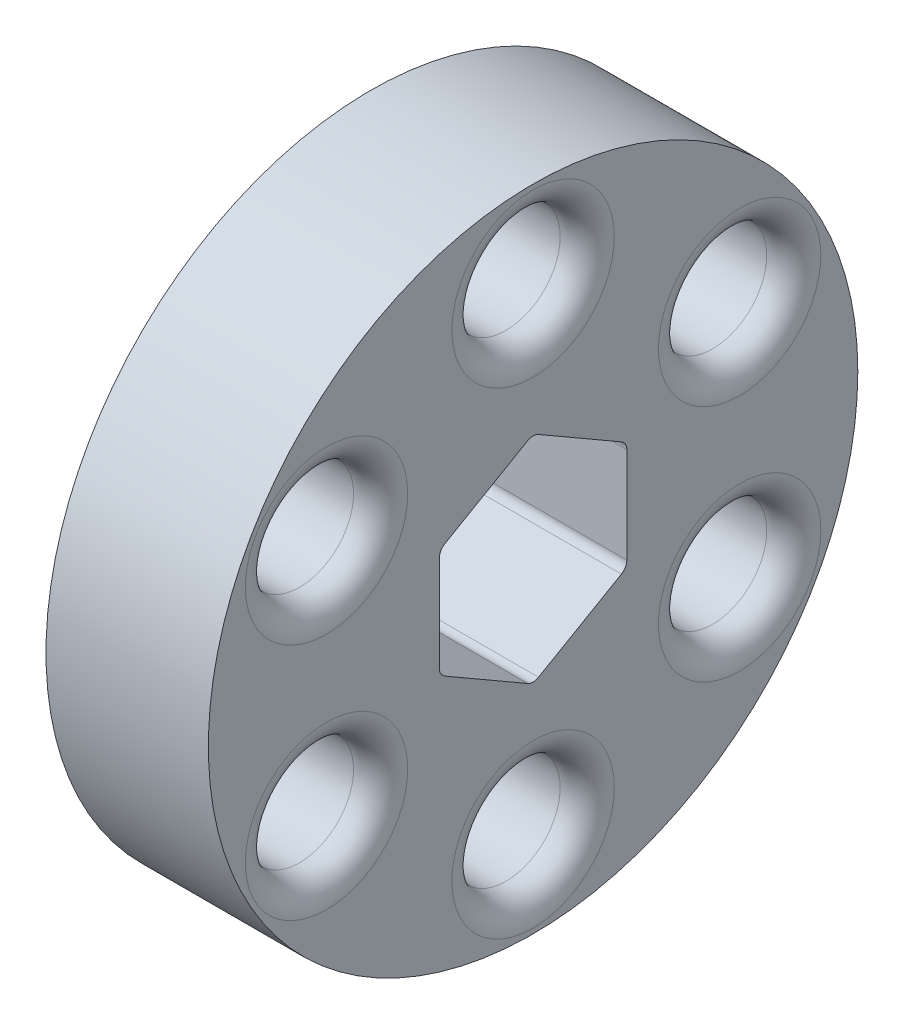
SolidWorks part; units mm, degrees
material "Náilon 6/10"
ref_plane "Plano frontal" through (0, 0, 0) normal (0, 0, 1) x (1, 0, 0)
ref_plane "Plano superior" through (0, 0, 0) normal (0, 1, 0) x (1, 0, 0)
ref_plane "Plano direito" through (0, 0, 0) normal (1, 0, 0) x (0, 0, -1)
sketch "Esboço1" plane through (0, 0, 0) normal (1, 0, 0) x (0, 0, -1)
  circle A0 centre (0, 0) radius 30
extrude "Ressalto-extrusão1" add sketch "Esboço1" along normal blind 15
sketch "Esboço2" plane through (15, 0, 0) normal (1, 0, 0) x (0, 0, -1)
  line L1 (0, 10) -> (-8.6603, 5)
  line L2 (-8.6603, 5) -> (-8.6603, -5)
  line L3 (-8.6603, -5) -> (0, -10)
  line L4 (0, -10) -> (8.6603, -5)
  line L5 (8.6603, -5) -> (8.6603, 5)
  line L6 (8.6603, 5) -> (0, 10)
  circle A0 centre (0, 0) radius 8.6603 construction
  circle A1 centre (0, 22.0357) radius 5
  circle A2 centre (19.0835, 11.0178) radius 5
  circle A3 centre (19.0835, -11.0178) radius 5
  circle A4 centre (0, -22.0357) radius 5
  circle A5 centre (-19.0835, -11.0178) radius 5
  circle A6 centre (-19.0835, 11.0178) radius 5
  point P24 (0, 0)
  dimension "D2" = 6
  dimension "D1" = 10
extrude "Corte-extrusão3" cut sketch "Esboço2" against normal through all
fillet "Filete1" radius 2.5 12 edges at (15, 11.0178, 14.0835) (0, 11.0178, 14.0835) (15, -11.0178, 14.0835) (0, -11.0178, 14.0835) (15, -22.0357, -5) (0, -22.0357, -5) (15, -11.0178, -24.0835) (0, -11.0178, -24.0835) (15, 11.0178, -24.0835) (0, 11.0178, -24.0835) (15, 22.0357, -5) (0, 22.0357, -5)
fillet "Filete2" radius 1 6 edges at (7.5, 10, 0) (7.5, 5, 8.6603) (7.5, -5, 8.6603) (7.5, -10, 0) (7.5, 5, -8.6603) (7.5, -5, -8.6603)
